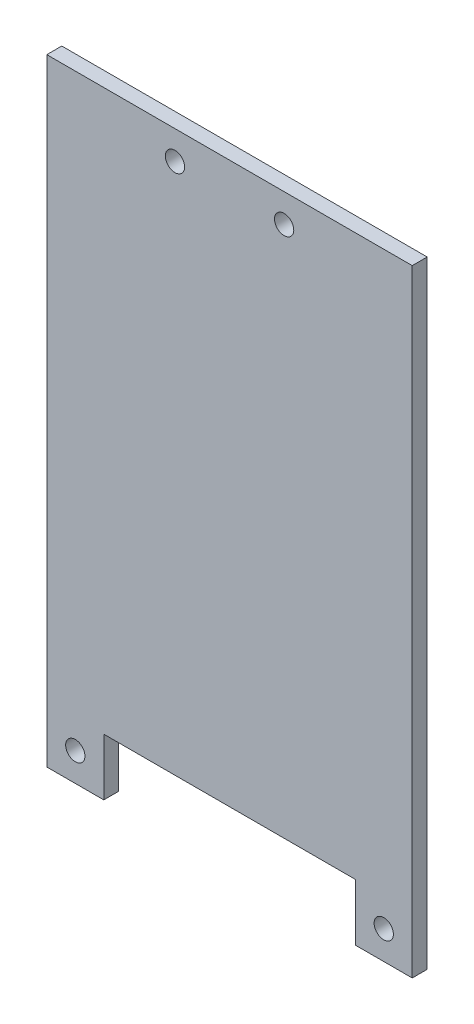
SolidWorks part; units mm, degrees
ref_plane "Front Plane" through (0, 0, 0) normal (0, 0, 1) x (1, 0, 0)
ref_plane "Top Plane" through (0, 0, 0) normal (0, 1, 0) x (1, 0, 0)
ref_plane "Right Plane" through (0, 0, 0) normal (1, 0, 0) x (0, 0, -1)
sketch "Model" plane through (0, 0, 0) normal (0, 0, 1) x (1, 0, 0)
  line L0 (6.6929, 65.8622) -> (6.6929, 61.9582) construction
  line L1 (6.6929, 61.9582) -> (6.6929, 65.8622) construction
  line L2 (6.6929, 65.8622) -> (6.6929, 72.5692) construction
  line L3 (13.6017, 63.7616) -> (25.1028, 63.7616) construction
  line L4 (25.1028, 63.7616) -> (25.1028, 70.5549) construction
  line L5 (13.6017, 63.7616) -> (13.6017, 70.6573) construction
  line L6 (19.3929, 61.9582) -> (19.3929, 73.0813) construction
  line L7 (31.0769, 61.9582) -> (31.0769, 73.1154) construction
  line L8 (3.1013, 4.7625) -> (35.6006, 4.7625) construction
  line L9 (35.6006, 4.7625) -> (35.6006, 0) construction
  line L11 (3.1013, 0) -> (3.1013, 4.7625) construction
  line L2429 (6.1011, 7.7622) -> (32.6009, 7.7622)
  line L2430 (32.6009, 7.7622) -> (32.6009, 1.7628)
  line L2431 (6.1011, 7.7622) -> (6.1011, 1.7628)
  line L2432 (38.6004, 66.7614) -> (38.6004, 1.7628)
  line L2433 (0.1016, 1.7628) -> (0.1016, 66.7614)
  line L2434 (32.6009, 1.7628) -> (38.6004, 1.7628)
  line L2435 (6.1011, 1.7628) -> (0.1016, 1.7628)
  line L2436 (38.6004, 66.7614) -> (0.1016, 66.7614)
  circle A4686 centre (13.6017, 63.7616) radius 1.016
  circle A4687 centre (25.1028, 63.7616) radius 1.016
  circle A4708 centre (35.6006, 4.7625) radius 1.016
  circle A4709 centre (3.1013, 4.7625) radius 1.016
  circle A4792 centre (6.1011, 7.7622) radius 0.0381
  circle A4793 centre (32.6009, 7.7622) radius 0.0381
  circle A4794 centre (32.6009, 7.7622) radius 0.0381
  circle A4795 centre (32.6009, 1.7628) radius 0.0381
  circle A4796 centre (6.1011, 7.7622) radius 0.0381
  circle A4797 centre (6.1011, 1.7628) radius 0.0381
  circle A4798 centre (38.6004, 66.7614) radius 0.0381
  circle A4799 centre (38.6004, 1.7628) radius 0.0381
  circle A4800 centre (0.1016, 1.7628) radius 0.0381
  circle A4801 centre (0.1016, 66.7614) radius 0.0381
  circle A4802 centre (32.6009, 1.7628) radius 0.0381
  circle A4803 centre (38.6004, 1.7628) radius 0.0381
  circle A4804 centre (6.1011, 1.7628) radius 0.0381
  circle A4805 centre (0.1016, 1.7628) radius 0.0381
  circle A4806 centre (38.6004, 66.7614) radius 0.0381
  circle A4807 centre (0.1016, 66.7614) radius 0.0381
  dimension "D1" = 11.5011
  dimension "D2" = 58.9991
  dimension "D3" = 10.4978
  dimension "D4" = 32.4993
extrude "Boss-Extrude1" add sketch "Model" along normal blind 1.5748 contours L2433 L2436 L2432 L2434 L2430 L2429 L2431 L2435
sketch "Sketch4" plane through (0, 0, 1.5748) normal (0, 0, 1) x (1, 0, 0)
  line L0 (19.351, 66.7614) -> (19.351, 7.7622) construction
  line L1 (38.6004, 66.7614) -> (0.1016, 66.7614) construction
  line L2 (6.1011, 7.7622) -> (32.6009, 7.7622) construction
  circle A0 centre (13.6017, 63.7616) radius 1.016
  circle A1 centre (25.1028, 63.7616) radius 1.016
  circle A2 centre (3.1013, 4.7625) radius 1.016
  circle A3 centre (35.6006, 4.7625) radius 1.016
extrude "Cut-Extrude1" cut sketch "Sketch4" against normal through all
